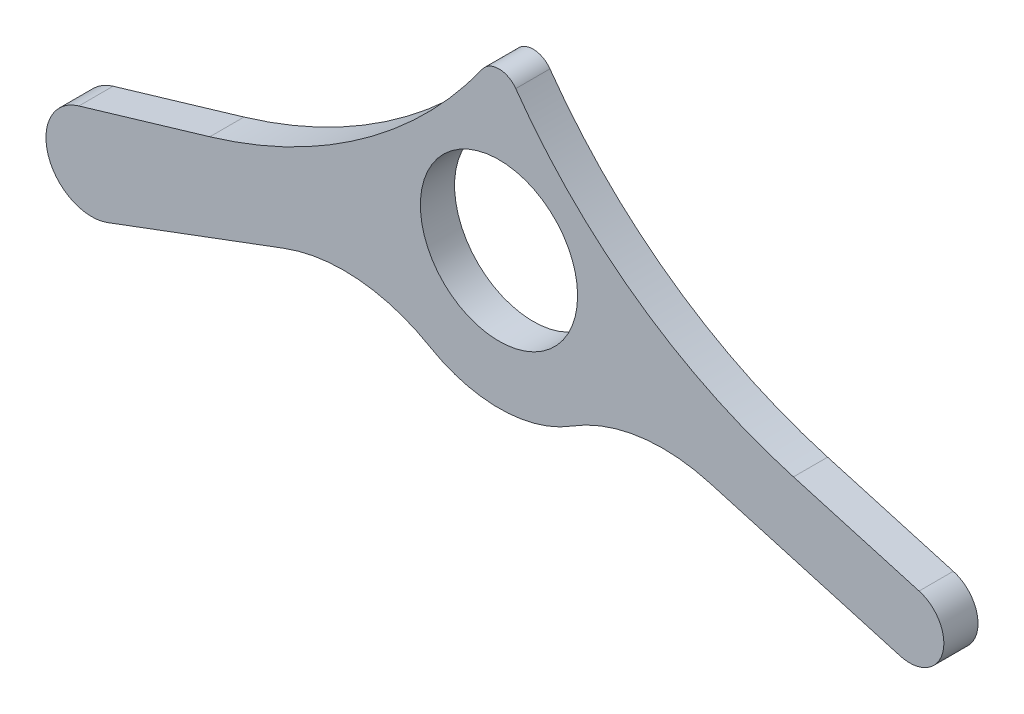
SolidWorks part; units mm, degrees
ref_plane "Front Plane" through (0, 0, 0) normal (0, 0, 1) x (1, 0, 0)
ref_plane "Top Plane" through (0, 0, 0) normal (0, 1, 0) x (1, 0, 0)
ref_plane "Right Plane" through (0, 0, 0) normal (1, 0, 0) x (0, 0, -1)
sketch "Sketch1" plane through (0, 0, 0) normal (0, 0, 1) x (1, 0, 0)
  line L0 (30.8635, -14.0515) -> (58.7007, -22.0336)
  line L1 (0, 0) -> (52.0863, 0) construction
  line L2 (0, 0) -> (60.0789, -17.2273) construction
  line L3 (0, 0) -> (0, -30.3047) construction
  line L4 (43.077, -7.1506) -> (61.457, -12.421)
  line L5 (1.3782, 4.8063) -> (61.457, -12.421) construction
  line L6 (-1.3782, -4.8063) -> (58.7007, -22.0336) construction
  line L7 (-42.3038, -6.7507) -> (-61.457, -12.421)
  line L9 (-57.241, -25.0942) -> (-31.4313, -15.4488)
  line L10 (0, 0) -> (-77.1771, 0) construction
  line L11 (0, 0) -> (-91.2315, -28.8405) construction
  circle A0 centre (0, 0) radius 11.5
  arc A1 (-10.0798, -17.2742) -> (10.6545, -16.9258) centre (0, 0) ccw
  arc A4 (61.457, -12.421) -> (58.7007, -22.0336) centre (60.0789, -17.2273) cw
  circle A7 centre (0, 0) radius 62.5 construction
  circle A8 centre (0, 0) radius 20 construction
  arc A9 (2.4519, 21.7286) -> (-2.4519, 21.7286) centre (0, 20) ccw
  arc A10 (2.4519, 21.7286) -> (43.077, -7.1506) centre (63.7498, 64.944) ccw
  arc A13 (-61.457, -12.421) -> (-57.241, -25.0942) centre (-59.5932, -18.8388) ccw
  arc A14 (30.8635, -14.0515) -> (10.6545, -16.9258) centre (23.9726, -38.083) ccw
  arc A15 (-10.0798, -17.2742) -> (-31.4313, -15.4488) centre (-22.6796, -38.8669) ccw
  arc A16 (-2.4519, 21.7286) -> (-42.3038, -6.7507) centre (-63.5941, 65.164) cw
  point P14 (-60.0789, -17.2273)
  point P18 (-58.9895, -20.6516)
  point P24 (-32.0025, 0)
  point P26 (-61.457, -12.421)
  point P28 (-61.457, -12.421)
  point P30 (-93.5479, -32.8364)
  point P33 (17.2366, -10.144)
  point P36 (-17.2366, -10.144)
  point P37 (0, 0)
  point P39 (-90.3116, -31.6035)
  dimension "D1" = 23
  dimension "D2" = 40
  dimension "D6" = 125
  dimension "D7" = 3
  dimension "D8" = 75
  dimension "D10" = 25
  dimension "D11" = 75
  dimension "D12" = 17.543
  dimension "D3" = 16
  dimension "D9" = 4
  dimension "D4" = 5
  dimension "D5" = 5
extrude "Boss-Extrude1" add sketch "Sketch1" along normal blind 5
